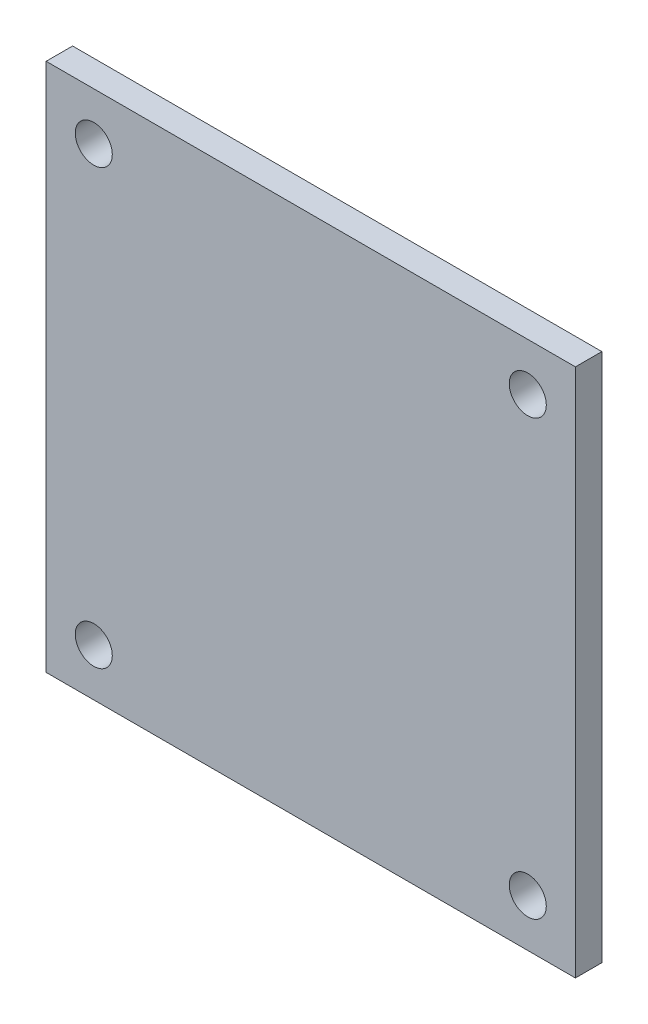
SolidWorks part; units mm, degrees
ref_plane "前视基准面" through (0, 0, 0) normal (0, 0, 1) x (1, 0, 0)
ref_plane "上视基准面" through (0, 0, 0) normal (0, 1, 0) x (1, 0, 0)
ref_plane "右视基准面" through (0, 0, 0) normal (1, 0, 0) x (0, 0, -1)
sketch "草图1" plane through (0, 0, 0) normal (0, 0, 1) x (1, 0, 0)
  line L1 (-50, -50) -> (50, -50)
  line L2 (-50, -50) -> (-50, 50)
  line L3 (-50, 50) -> (50, 50)
  line L4 (50, -50) -> (50, 50)
  line L5 (-50, -50) -> (50, 50) construction
  line L6 (-50, 50) -> (50, -50) construction
  point P0 (0, 0)
  dimension "D1" = 100
  dimension "D2" = 100
extrude "凸台-拉伸1" add sketch "草图1" along normal blind 5
sketch "草图2" plane through (0, 0, 5) normal (0, 0, 1) x (1, 0, 0)
  line L0 (-50, 50) -> (-50, -50) construction
  line L1 (50, 50) -> (-50, 50) construction
  circle A0 centre (-41, 41) radius 3.5
  circle A1 centre (-41, -41) radius 3.5
  circle A2 centre (41, -41) radius 3.5
  circle A3 centre (41, 41) radius 3.5
  point P6 (0, 0)
  point P15 (0, 0)
  dimension "D1" = 7
  dimension "D2" = 9
  dimension "D3" = 9
  dimension "D4" = 4
extrude "切除-拉伸1" cut sketch "草图2" against normal up to surface (5 mm away) up to face at (0, 0, 0)
